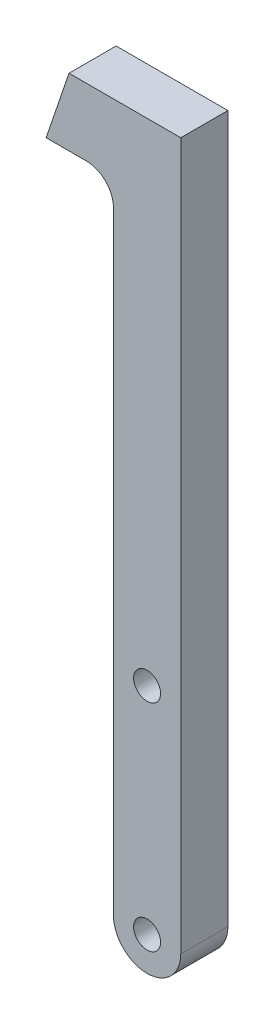
SolidWorks part; units mm, degrees
ref_plane "Plan de face" through (0, 0, 0) normal (0, 0, 1) x (1, 0, 0)
ref_plane "Plan de dessus" through (0, 0, 0) normal (0, 1, 0) x (1, 0, 0)
ref_plane "Plan de droite" through (0, 0, 0) normal (1, 0, 0) x (0, 0, -1)
sketch "Esquisse1" plane through (0, 0, 0) normal (0, 0, 1) x (1, 0, 0)
  line L0 (0, 0) -> (10, 0)
  line L1 (10, 0) -> (10, -52.5)
  line L2 (0, 0) -> (0, -5)
  line L3 (0, -5) -> (5, -5)
  line L4 (5, -5) -> (5, -52.5)
  arc A0 (5, -52.5) -> (10, -52.5) centre (7.5, -52.5) ccw
  point P8 (7.5, -55)
  point P9 (2.5, -5)
  dimension "D1" = 50
  dimension "D2" = 10
  dimension "D3" = 5
  dimension "D4" = 5
extrude "Boss.-Extru.1" add sketch "Esquisse1" along normal blind 3.5
sketch "Esquisse3" plane through (0, 0, 0) normal (0, 0, -1) x (-1, 0, 0)
  line L0 (-10, -52.5) -> (-5, -52.5) construction
  arc A0 (-10, -52.5) -> (-5, -52.5) centre (-7.5, -52.5) ccw construction
  circle A1 centre (-7.5, -52.5) radius 1
  dimension "D1" = 2
extrude "Enlèv. mat.-Extru.1" cut sketch "Esquisse3" against normal blind 4
sketch "Esquisse4" plane through (0, 0, 3.5) normal (0, 0, 1) x (1, 0, 0)
  line L0 (7.5, -51.5) -> (7.5, -36.5) construction
  circle A0 centre (7.5, -52.5) radius 1 construction
  circle A1 centre (7.5, -36.5) radius 1
  dimension "D2" = 2
  dimension "D1" = 15
extrude "Enlèv. mat.-Extru.2" cut sketch "Esquisse4" against normal blind 10
sketch "Esquisse5" plane through (0, 0, 3.5) normal (0, 0, 1) x (1, 0, 0)
  line L0 (0, 0) -> (1.7009, 0)
  line L1 (10, 0) -> (0, 0) construction
  line L2 (1.7009, 0) -> (0, -5)
  line L3 (0, -5) -> (0, 0)
extrude "Enlèv. mat.-Extru.3" cut sketch "Esquisse5" against normal through all
fillet "Congé1" radius 2 1 edges at (5, -5, 1.75)
